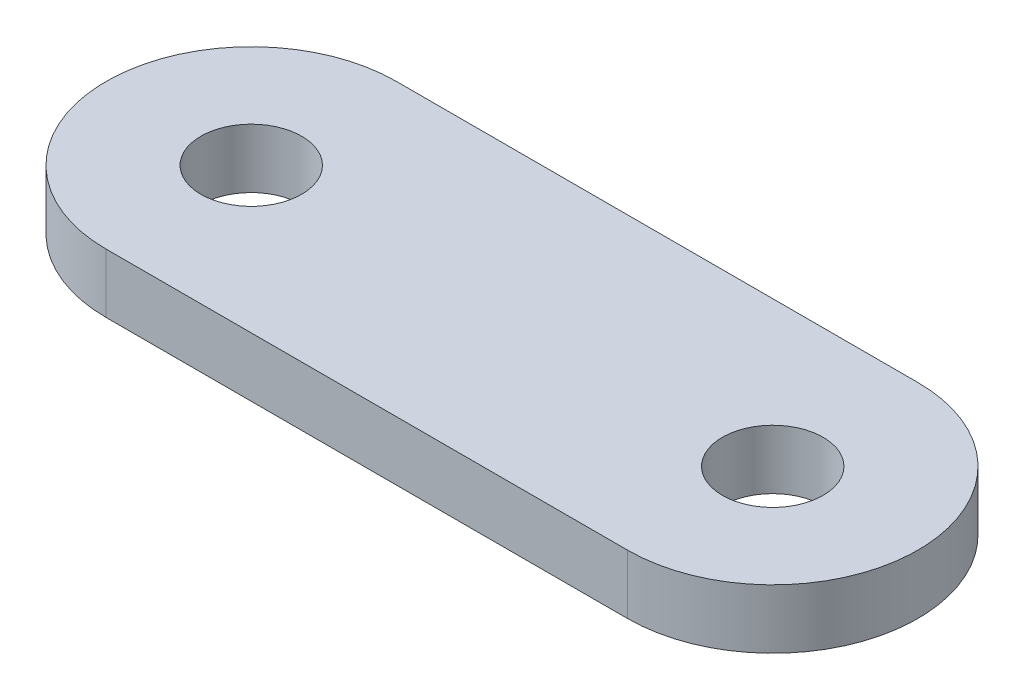
SolidWorks part; units mm, degrees
ref_plane "Front Plane" through (0, 0, 0) normal (0, 0, 1) x (1, 0, 0)
ref_plane "Top Plane" through (0, 0, 0) normal (0, 1, 0) x (1, 0, 0)
ref_plane "Right Plane" through (0, 0, 0) normal (1, 0, 0) x (0, 0, -1)
sketch "Sketch1" plane through (0, 0, 0) normal (0, 1, 0) x (1, 0, 0)
  line L0 (0, 0) -> (17.6, 0) construction
  line L1 (0, 4.9) -> (17.6, 4.9)
  line L2 (0, -4.9) -> (17.6, -4.9)
  arc A0 (0, 4.9) -> (0, -4.9) centre (0, 0) ccw
  arc A1 (17.6, -4.9) -> (17.6, 4.9) centre (17.6, 0) ccw
  circle A2 centre (0, 0) radius 1.7
  circle A3 centre (17.6, 0) radius 1.7
  point P3 (8.8, 0)
  dimension "D1" = 3.4
  dimension "D3" = 3.2
  dimension "D2" = 17.6
extrude "Boss-Extrude1" add sketch "Sketch1" along normal blind 2
